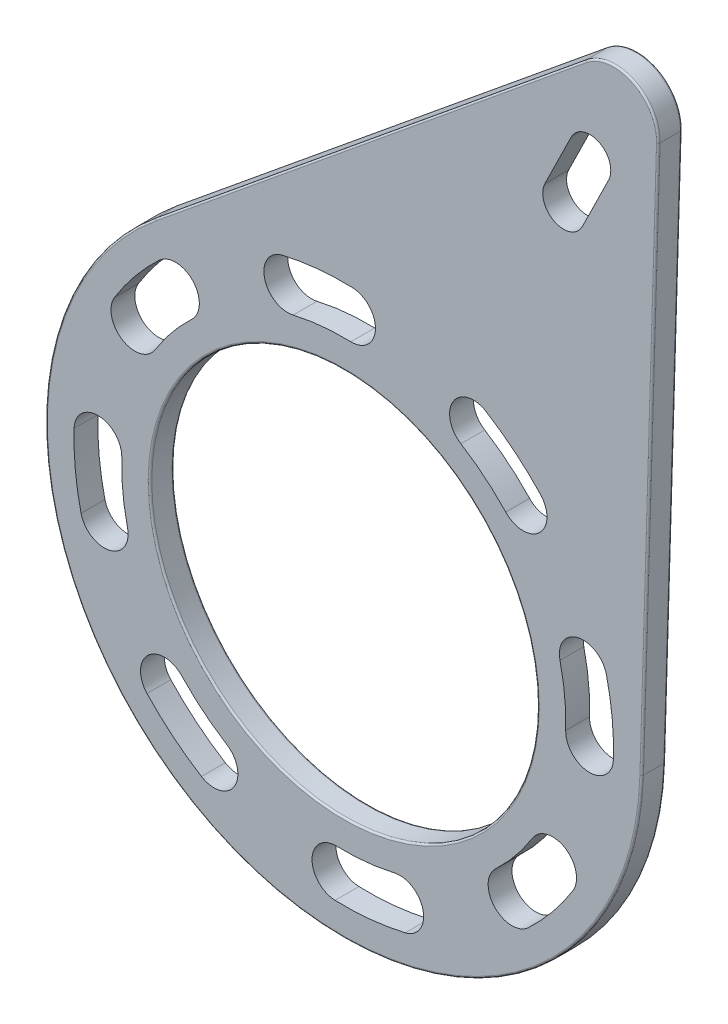
SolidWorks part; units mm, degrees
ref_plane "Ön Düzlem" through (0, 0, 0) normal (0, 0, 1) x (1, 0, 0)
ref_plane "Üst Düzlem" through (0, 0, 0) normal (0, 1, 0) x (1, 0, 0)
ref_plane "Sağ Düzlem" through (0, 0, 0) normal (1, 0, 0) x (0, 0, -1)
sketch "Sketch1" plane through (0, 0, 0) normal (0, 0, 1) x (1, 0, 0)
  line L0 (0, 0) -> (58.6666, 119.195) construction
  line L1 (0, 0) -> (50, 0) construction
  line L2 (-76.6549, -17.9994) -> (9.8368, -60.5697) construction
  line L3 (58.6666, 119.195) -> (57.2752, 116.368) construction
  line L4 (49.9777, -1.4917) -> (52.7605, 91.7405)
  line L5 (13.3842, 116.0144) -> (67.063, 89.5942) construction
  line L6 (-31.6675, 38.6932) -> (40.5138, 97.7683)
  line L7 (41.2895, 83.8894) -> (36.8735, 74.9173) construction
  line L8 (44.4297, 82.3438) -> (40.0138, 73.3717)
  line L9 (38.1493, 85.435) -> (33.7333, 76.4628)
  line L10 (1.6926, 107.2795) -> (5.6781, 105.3179) construction
  line L11 (-18.8847, -26.4503) -> (-29.0533, -40.6928) construction
  circle A0 centre (0, 0) radius 32.5
  circle A1 centre (0, 0) radius 50
  circle A2 centre (45.2639, 91.9643) radius 7.5
  arc A3 (44.4297, 82.3438) -> (38.1493, 85.435) centre (41.2895, 83.8894) ccw
  arc A4 (33.7333, 76.4628) -> (40.0138, 73.3717) centre (36.8735, 74.9173) ccw
  circle A5 centre (0, 0) radius 41.25 construction
  arc A6 (-28.2206, 30.0859) -> (-35.0458, 21.7567) centre (0, 0) ccw construction
  arc A7 (-30.9572, 33.0033) -> (-38.4442, 23.8664) centre (0, 0) ccw
  arc A8 (-25.4841, 27.1684) -> (-31.6474, 19.6469) centre (0, 0) ccw
  arc A9 (-25.4841, 27.1684) -> (-30.9572, 33.0033) centre (-28.2206, 30.0859) ccw
  arc A10 (-38.4442, 23.8664) -> (-31.6474, 19.6469) centre (-35.0458, 21.7567) ccw
  arc A11 (1.3189, 41.2289) -> (-9.3969, 40.1654) centre (0, 0) ccw construction
  arc A12 (1.4468, 45.2269) -> (-10.3081, 44.0603) centre (0, 0) ccw
  arc A13 (1.191, 37.231) -> (-8.4856, 36.2706) centre (0, 0) ccw
  arc A14 (1.191, 37.231) -> (1.4468, 45.2269) centre (1.3189, 41.2289) ccw
  arc A15 (-10.3081, 44.0603) -> (-8.4856, 36.2706) centre (-9.3969, 40.1654) ccw
  arc A16 (30.0859, 28.2206) -> (21.7567, 35.0458) centre (0, 0) ccw construction
  arc A17 (33.0033, 30.9572) -> (23.8664, 38.4442) centre (0, 0) ccw
  arc A18 (27.1684, 25.4841) -> (19.6469, 31.6474) centre (0, 0) ccw
  arc A19 (27.1684, 25.4841) -> (33.0033, 30.9572) centre (30.0859, 28.2206) ccw
  arc A20 (23.8664, 38.4442) -> (19.6469, 31.6474) centre (21.7567, 35.0458) ccw
  arc A21 (41.2289, -1.3189) -> (40.1654, 9.3969) centre (0, 0) ccw construction
  arc A22 (45.2269, -1.4468) -> (44.0603, 10.3081) centre (0, 0) ccw
  arc A23 (37.231, -1.191) -> (36.2706, 8.4856) centre (0, 0) ccw
  arc A24 (37.231, -1.191) -> (45.2269, -1.4468) centre (41.2289, -1.3189) ccw
  arc A25 (44.0603, 10.3081) -> (36.2706, 8.4856) centre (40.1654, 9.3969) ccw
  arc A26 (28.2206, -30.0859) -> (35.0458, -21.7567) centre (0, 0) ccw construction
  arc A27 (30.9572, -33.0033) -> (38.4442, -23.8664) centre (0, 0) ccw
  arc A28 (25.4841, -27.1684) -> (31.6474, -19.6469) centre (0, 0) ccw
  arc A29 (25.4841, -27.1684) -> (30.9572, -33.0033) centre (28.2206, -30.0859) ccw
  arc A30 (38.4442, -23.8664) -> (31.6474, -19.6469) centre (35.0458, -21.7567) ccw
  arc A31 (-1.3189, -41.2289) -> (9.3969, -40.1654) centre (0, 0) ccw construction
  arc A32 (-1.4468, -45.2269) -> (10.3081, -44.0603) centre (0, 0) ccw
  arc A33 (-1.191, -37.231) -> (8.4856, -36.2706) centre (0, 0) ccw
  arc A34 (-1.191, -37.231) -> (-1.4468, -45.2269) centre (-1.3189, -41.2289) ccw
  arc A35 (10.3081, -44.0603) -> (8.4856, -36.2706) centre (9.3969, -40.1654) ccw
  arc A36 (-30.0859, -28.2206) -> (-21.7567, -35.0458) centre (0, 0) ccw construction
  arc A37 (-33.0033, -30.9572) -> (-23.8664, -38.4442) centre (0, 0) ccw
  arc A38 (-27.1684, -25.4841) -> (-19.6469, -31.6474) centre (0, 0) ccw
  arc A39 (-27.1684, -25.4841) -> (-33.0033, -30.9572) centre (-30.0859, -28.2206) ccw
  arc A40 (-23.8664, -38.4442) -> (-19.6469, -31.6474) centre (-21.7567, -35.0458) ccw
  arc A41 (-41.2289, 1.3189) -> (-40.1654, -9.3969) centre (0, 0) ccw construction
  arc A42 (-45.2269, 1.4468) -> (-44.0603, -10.3081) centre (0, 0) ccw
  arc A43 (-37.231, 1.191) -> (-36.2706, -8.4856) centre (0, 0) ccw
  arc A44 (-37.231, 1.191) -> (-45.2269, 1.4468) centre (-41.2289, 1.3189) ccw
  arc A45 (-44.0603, -10.3081) -> (-36.2706, -8.4856) centre (-40.1654, -9.3969) ccw
  point P19 (39.0815, 79.4033)
  point P33 (-31.9062, 26.1449)
  point P43 (-4.0738, 41.0483)
  point P50 (26.1449, 31.9062)
  point P57 (41.0483, 4.0738)
  point P64 (31.9062, -26.1449)
  point P71 (4.0738, -41.0483)
  point P78 (-26.1449, -31.9062)
  point P85 (-41.0483, -4.0738)
  point P90 (0, 0)
  dimension "D1" = 100
  dimension "D2" = 65
  dimension "D4" = 15
  dimension "D5" = 13
  dimension "D11" = 41.25
  dimension "D3" = 160
  dimension "D6" = 7
  dimension "D7" = 10
  dimension "D8" = 8.75
  dimension "D9" = 8
  dimension "D10" = 15
  dimension "D12" = 8
extrude "Boss-Extrude1" add sketch "Sketch1" along normal blind 4 contours A4 L9 A2 L6 A1 L4 L8 | A1 A45 A42 A44 A43 A40 A37 A39 A38 A35 A32 A34 A33 A30 A27 A29 A28 A25 A22 A24 A23 A20 A17 A19 A18 A15 A12 A14 A13 A10 A7 A9 A8 A0 | A3 L8 A2 L9
fillet "Fillet1" radius 0.3 10 edges at (-22.0799, -44.8606, 0) (-22.0799, -44.8606, 4) (51.3691, 45.1244, 0) (51.3691, 45.1244, 4) (48.5759, 98.6934, 0) (48.5759, 98.6934, 4) (32.5, 0, 4) (32.5, 0, 0) (4.4231, 68.2308, 0) (4.4231, 68.2308, 4)
ref_plane "Plane1" through (0, 0, 0) normal (-0.8972, 0.4416, 0) x (0, 0, 1)
